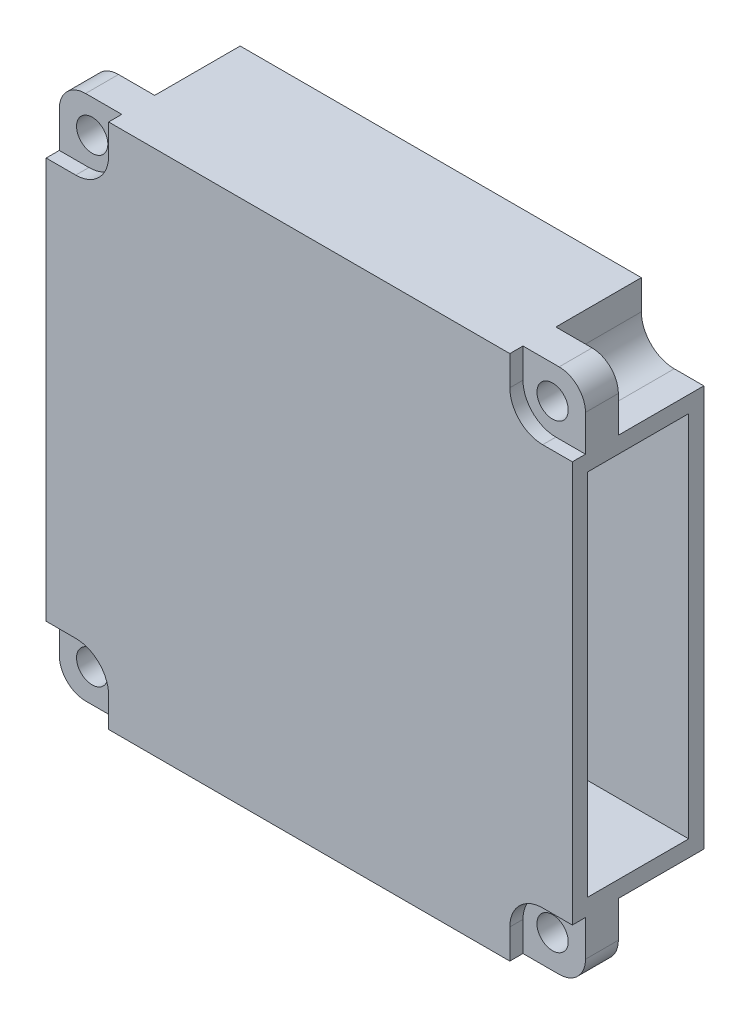
SolidWorks part; units mm, degrees
ref_plane "前视基准面" through (0, 0, 0) normal (0, 0, 1) x (1, 0, 0)
ref_plane "上视基准面" through (0, 0, 0) normal (0, 1, 0) x (1, 0, 0)
ref_plane "右视基准面" through (0, 0, 0) normal (1, 0, 0) x (0, 0, -1)
sketch "草图1" plane through (0, 0, 0) normal (0, 0, 1) x (1, 0, 0)
  line L1 (-20, -20) -> (20, -20)
  line L2 (-20, -20) -> (-20, 20)
  line L3 (-20, 20) -> (20, 20)
  line L4 (20, -20) -> (20, 20)
  line L5 (-20, -20) -> (20, 20) construction
  line L6 (-20, 20) -> (20, -20) construction
  point P0 (0, 0)
  dimension "D1" = 40
extrude "凸台-拉伸1" add sketch "草图1" along normal mid plane 10
sketch "草图2" plane through (20, 0, 0) normal (1, 0, 0) x (0, 0, -1)
  line L0 (-5, 20) -> (5, 20) construction
  line L1 (-3.85, -14) -> (3.85, -14)
  line L2 (-3.85, -14) -> (-3.85, 14)
  line L3 (-3.85, 14) -> (3.85, 14)
  line L4 (3.85, -14) -> (3.85, 14)
  line L5 (-3.85, -14) -> (3.85, 14) construction
  line L6 (-3.85, 14) -> (3.85, -14) construction
  point P0 (0, 0)
  point P9 (0, 20)
  dimension "D1" = 28
  dimension "D2" = 7.7
extrude "切除-拉伸1" cut sketch "草图2" against normal blind 10
sketch "草图3" plane through (0, 0, -5) normal (0, 0, -1) x (-1, 0, 0)
  line L0 (15.25, 20) -> (15.25, 17.75)
  line L1 (-20, 20) -> (20, 20) construction
  line L2 (17.75, 15.25) -> (20, 15.25)
  line L3 (20, 20) -> (20, -20) construction
  line L4 (0, 20) -> (0, 0) construction
  line L5 (0, 0) -> (20, 0) construction
  line L6 (17.75, -15.25) -> (20, -15.25)
  line L7 (15.25, -20) -> (15.25, -17.75)
  line L8 (-15.25, -20) -> (-15.25, -17.75)
  line L9 (-17.75, -15.25) -> (-20, -15.25)
  line L10 (-17.75, 15.25) -> (-20, 15.25)
  line L11 (-15.25, 20) -> (-15.25, 17.75)
  arc A0 (15.25, 17.75) -> (17.75, 15.25) centre (17.75, 17.75) ccw
  arc A1 (15.25, -17.75) -> (17.75, -15.25) centre (17.75, -17.75) cw
  arc A2 (-15.25, -17.75) -> (-17.75, -15.25) centre (-17.75, -17.75) ccw
  arc A3 (-15.25, 17.75) -> (-17.75, 15.25) centre (-17.75, 17.75) cw
  point P22 (15.25, 15.25)
  line M4 (-20, 20) -> (-20, -20)
  line M5 (-20, -20) -> (20, -20)
  line M6 (20, -20) -> (20, 20)
  line M7 (20, 20) -> (-20, 20)
  dimension "D2" = 2.5
  dimension "D1" = 4.75
extrude "切除-拉伸2" cut sketch "草图3" against normal offset from surface (6.5 mm away) 3.5 contours L0 A0 L2 M6 M7 | A1 L7 L6 M5 M6 | L8 A2 L9 M4 M5 | A3 L11 L10 M7 M4 up to face at (0, 0, 5)
fillet "圆角1" radius 2 4 edges at (-20, 20, 3.25) (-20, -20, 3.25) (20, -20, 3.25) (20, 20, 3.25)
sketch "草图4" plane through (0, 0, 5) normal (0, 0, 1) x (1, 0, 0)
  line L0 (20, -15.25) -> (20, -18) construction
  line L1 (18, -20) -> (15.25, -20) construction
  line L2 (15.25, -20) -> (15.25, -17.75) construction
  line L3 (17.75, -15.25) -> (20, -15.25) construction
  line L4 (-15.25, -20) -> (-18, -20) construction
  line L5 (-20, -18) -> (-20, -15.25) construction
  line L6 (-20, -15.25) -> (-17.75, -15.25) construction
  line L7 (-15.25, -17.75) -> (-15.25, -20) construction
  line L8 (15.25, 20) -> (18, 20) construction
  line L9 (20, 18) -> (20, 15.25) construction
  line L10 (20, 15.25) -> (17.75, 15.25) construction
  line L11 (15.25, 17.75) -> (15.25, 20) construction
  line L12 (-20, 15.25) -> (-20, 18) construction
  line L13 (-18, 20) -> (-15.25, 20) construction
  line L14 (-15.25, 20) -> (-15.25, 17.75) construction
  line L15 (-17.75, 15.25) -> (-20, 15.25) construction
  line L16 (20, -15.25) -> (20, -18)
  line L17 (18, -20) -> (15.25, -20)
  line L18 (15.25, -20) -> (15.25, -17.75)
  line L19 (17.75, -15.25) -> (20, -15.25)
  line L20 (-15.25, -20) -> (-18, -20)
  line L21 (-20, -18) -> (-20, -15.25)
  line L22 (-20, -15.25) -> (-17.75, -15.25)
  line L23 (-15.25, -17.75) -> (-15.25, -20)
  line L24 (15.25, 20) -> (18, 20)
  line L25 (20, 18) -> (20, 15.25)
  line L26 (20, 15.25) -> (17.75, 15.25)
  line L27 (15.25, 17.75) -> (15.25, 20)
  line L28 (-20, 15.25) -> (-20, 18)
  line L29 (-18, 20) -> (-15.25, 20)
  line L30 (-15.25, 20) -> (-15.25, 17.75)
  line L31 (-17.75, 15.25) -> (-20, 15.25)
  arc A0 (18, -20) -> (20, -18) centre (18, -18) ccw construction
  arc A1 (17.75, -15.25) -> (15.25, -17.75) centre (17.75, -17.75) ccw construction
  arc A2 (-20, -18) -> (-18, -20) centre (-18, -18) ccw construction
  arc A3 (-15.25, -17.75) -> (-17.75, -15.25) centre (-17.75, -17.75) ccw construction
  arc A4 (20, 18) -> (18, 20) centre (18, 18) ccw construction
  arc A5 (15.25, 17.75) -> (17.75, 15.25) centre (17.75, 17.75) ccw construction
  arc A6 (-18, 20) -> (-20, 18) centre (-18, 18) ccw construction
  arc A7 (-17.75, 15.25) -> (-15.25, 17.75) centre (-17.75, 17.75) ccw construction
  arc A8 (18, -20) -> (20, -18) centre (18, -18) ccw
  arc A9 (17.75, -15.25) -> (15.25, -17.75) centre (17.75, -17.75) ccw
  arc A10 (-20, -18) -> (-18, -20) centre (-18, -18) ccw
  arc A11 (-15.25, -17.75) -> (-17.75, -15.25) centre (-17.75, -17.75) ccw
  arc A12 (20, 18) -> (18, 20) centre (18, 18) ccw
  arc A13 (15.25, 17.75) -> (17.75, 15.25) centre (17.75, 17.75) ccw
  arc A14 (-18, 20) -> (-20, 18) centre (-18, 18) ccw
  arc A15 (-17.75, 15.25) -> (-15.25, 17.75) centre (-17.75, 17.75) ccw
extrude "切除-拉伸3" cut sketch "草图4" against normal blind 1
sketch "草图5" plane through (0, 0, 4) normal (0, 0, 1) x (1, 0, 0)
  line L0 (0, 17.5) -> (0, 0) construction
  line L5 (-17.5, -17.5) -> (17.5, -17.5) construction
  line L6 (-17.5, -17.5) -> (-17.5, 17.5) construction
  line L7 (-17.5, 17.5) -> (17.5, 17.5) construction
  line L8 (17.5, -17.5) -> (17.5, 17.5) construction
  line L9 (-17.5, -17.5) -> (17.5, 17.5) construction
  line L10 (-17.5, 17.5) -> (17.5, -17.5) construction
  line L11 (0, 0) -> (17.5, 0) construction
  circle A0 centre (-17.5, 17.5) radius 1.189
  circle A1 centre (-17.5, -17.5) radius 1.189
  circle A2 centre (17.5, -17.5) radius 1.189
  circle A3 centre (17.5, 17.5) radius 1.189
  point P0 (0, 0)
  dimension "D2" = 2.378
  dimension "D1" = 35
extrude "切除-拉伸4" cut sketch "草图5" against normal up to next
sketch "草图6" plane through (0, 0, -5) normal (0, 0, -1) x (-1, 0, 0)
  line L0 (15.25, -20) -> (-15.25, -20) construction
  line L1 (-20, -15.25) -> (-20, 15.25) construction
  circle A0 centre (-0.5, -4) radius 14
  dimension "D1" = 16
  dimension "D3" = 28
  dimension "D2" = 19.5
extrude "切除-拉伸5" cut sketch "草图6" against normal blind 1
